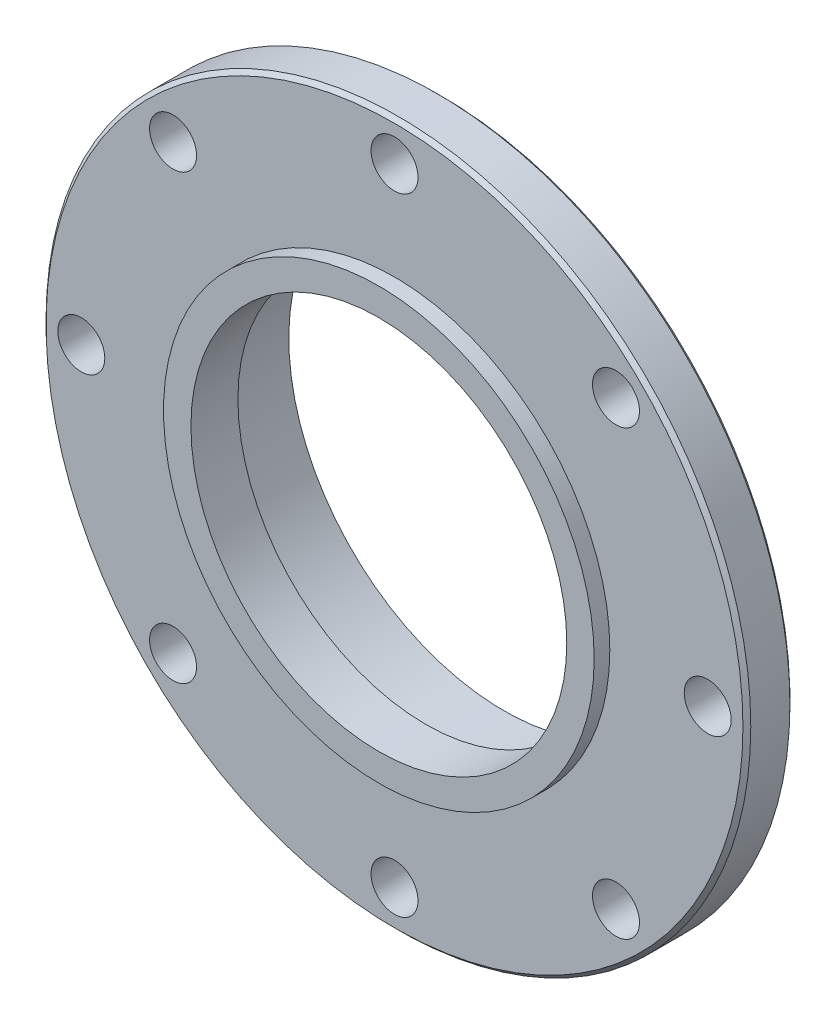
SolidWorks part; units mm, degrees
ref_plane "前视基准面" through (0, 0, 0) normal (0, 0, 1) x (1, 0, 0)
ref_plane "上视基准面" through (0, 0, 0) normal (0, 1, 0) x (1, 0, 0)
ref_plane "右视基准面" through (0, 0, 0) normal (1, 0, 0) x (0, 0, -1)
sketch "草图1" plane through (0, 0, 0) normal (0, 0, 1) x (1, 0, 0)
  circle A0 centre (0, 0) radius 45
  dimension "D1" = 90
extrude "拉伸1" add sketch "草图1" along normal blind 14
sketch "草图2" plane through (0, 0, 14) normal (0, 0, 1) x (1, 0, 0)
  circle A0 centre (0, 0) radius 27.5
  dimension "D1" = 55
extrude "拉伸2" add sketch "草图2" along normal blind 2
sketch "草图3" plane through (0, 0, 16) normal (0, 0, 1) x (1, 0, 0)
  circle A0 centre (0, 0) radius 24
  dimension "D1" = 48
extrude "切除-拉伸1" cut sketch "草图3" against normal through all
sketch "草图4" plane through (0, 0, 0) normal (0, 0, -1) x (-1, 0, 0)
  circle A1 centre (0, 40) radius 3
  circle A2 centre (28.2843, 28.2843) radius 3
  circle A3 centre (40, 0) radius 3
  circle A4 centre (28.2843, -28.2843) radius 3
  circle A5 centre (0, -40) radius 3
  circle A6 centre (-28.2843, -28.2843) radius 3
  circle A7 centre (-40, 0) radius 3
  circle A8 centre (-28.2843, 28.2843) radius 3
  dimension "D2" = 80
extrude "切除-拉伸2" cut sketch "草图4" against normal blind 15
chamfer "倒角1" distance 0.5 angle 45 2 edges at (45, 0, 14) (45, 0, 0)
sketch "草图6" plane through (0, 0, 0) normal (0, 0, -1) x (-1, 0, 0)
  circle A0 centre (0, 0) radius 48.0168
  circle A1 centre (0, 0) radius 30
  dimension "D1" = 60
extrude "切除-拉伸4" cut sketch "草图6" against normal blind 8
chamfer "倒角2" distance 0.5 angle 45 2 edges at (-45, 0, 8) (-30, 0, 0)
sketch "草图7" plane through (0, 0, 0) normal (0, 0, -1) x (-1, 0, 0)
  circle A0 centre (0, 0) radius 27.5
  dimension "D1" = 55
extrude "切除-拉伸7" cut sketch "草图7" against normal blind 10
fillet "圆角1" radius 5 1 edges at (-30, 0, 8)
